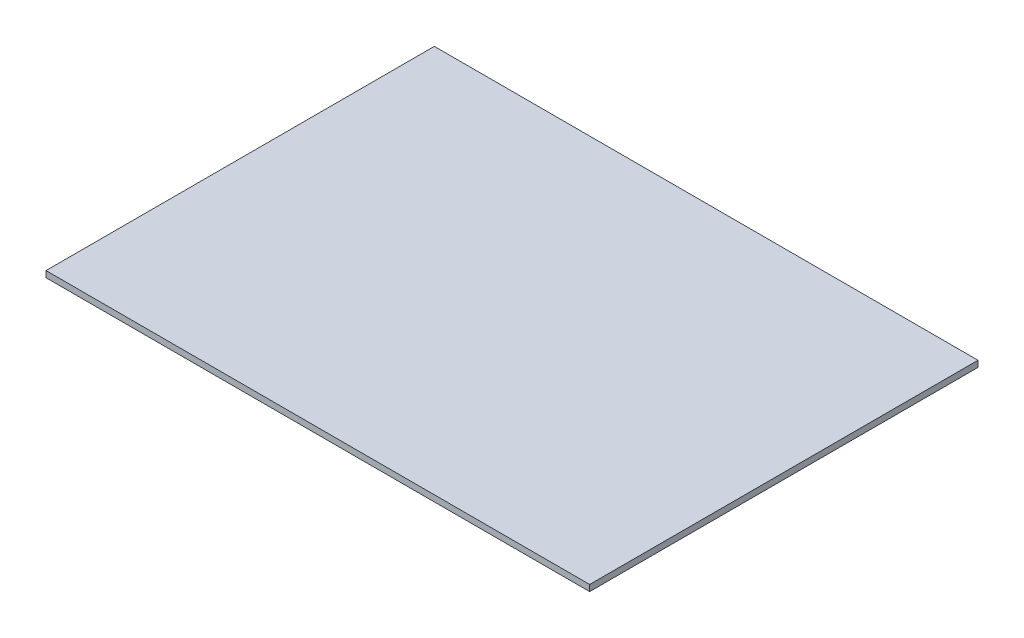
SolidWorks part; units mm, degrees
material "3.1645 (EN AW-2007)"
ref_plane "Front Plane" through (0, 0, 0) normal (0, 0, 1) x (1, 0, 0)
ref_plane "Top Plane" through (0, 0, 0) normal (0, 1, 0) x (1, 0, 0)
ref_plane "Right Plane" through (0, 0, 0) normal (1, 0, 0) x (0, 0, -1)
sketch "Sketch1" plane through (0, 0, 0) normal (0, 1, 0) x (1, 0, 0)
  line L1 (350, -250) -> (-350, -250)
  line L2 (350, -250) -> (350, 250)
  line L3 (350, 250) -> (-350, 250)
  line L4 (-350, -250) -> (-350, 250)
  line L5 (350, -250) -> (-350, 250) construction
  line L6 (350, 250) -> (-350, -250) construction
  point P0 (0, 0)
  dimension "D1" = 500
  dimension "D2" = 700
extrude "Boss-Extrude1" add sketch "Sketch1" along normal blind 8
